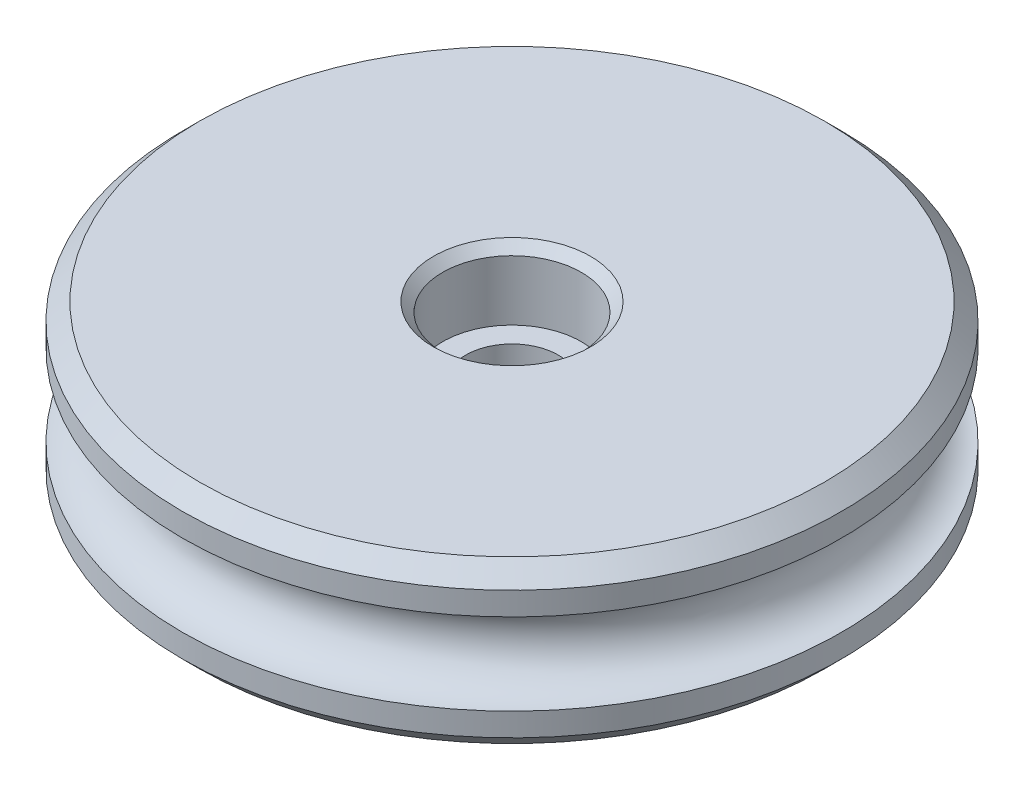
SolidWorks part; units mm, degrees
material "ABS"
ref_plane "Front Plane" through (0, 0, 0) normal (0, 0, 1) x (1, 0, 0)
ref_plane "Top Plane" through (0, 0, 0) normal (0, 1, 0) x (1, 0, 0)
ref_plane "Right Plane" through (0, 0, 0) normal (1, 0, 0) x (0, 0, -1)
sketch "Sketch1" plane through (0, 0, 0) normal (1, 0, 0) x (0, 0, -1)
  line L0 (0, 19.0174) -> (0, -19.7603) construction
  line L1 (-3, 3.5) -> (-13.5274, 3.5)
  line L3 (-14.2621, 0) -> (-12.4968, 0) construction
  line L4 (-12.4968, 0) -> (-2, 0)
  line L7 (-2, 0) -> (-2, 0.5)
  line L8 (-2, 0.5) -> (-3, 0.5)
  line L9 (-3, 0.5) -> (-3, 3.5)
  line L10 (-14.2621, 1.7653) -> (-14.2621, 2.7653)
  line L11 (-14.2621, 2.7653) -> (-13.5274, 3.5)
  arc A0 (-12.4968, 0) -> (-14.2621, 1.7653) centre (-14.2621, 0) ccw
  dimension "D1" = 3.5306
  dimension "D2" = 24.9936
  dimension "D3" = 3
  dimension "D4" = 0.5
  dimension "D5" = 1
  dimension "D6" = 6
  dimension "D7" = 1
  dimension "D8" = 45
revolve "Revolve1" add sketch "Sketch1" angle 360 about L0
mirror "Mirror1" about plane through (0, 0, 0) normal (0, 1, 0) of "Revolve1"
chamfer "Chamfer1" distance 0.4 angle 45 2 edges at (0, 3.5, 3) (0, -3.5, 3)
